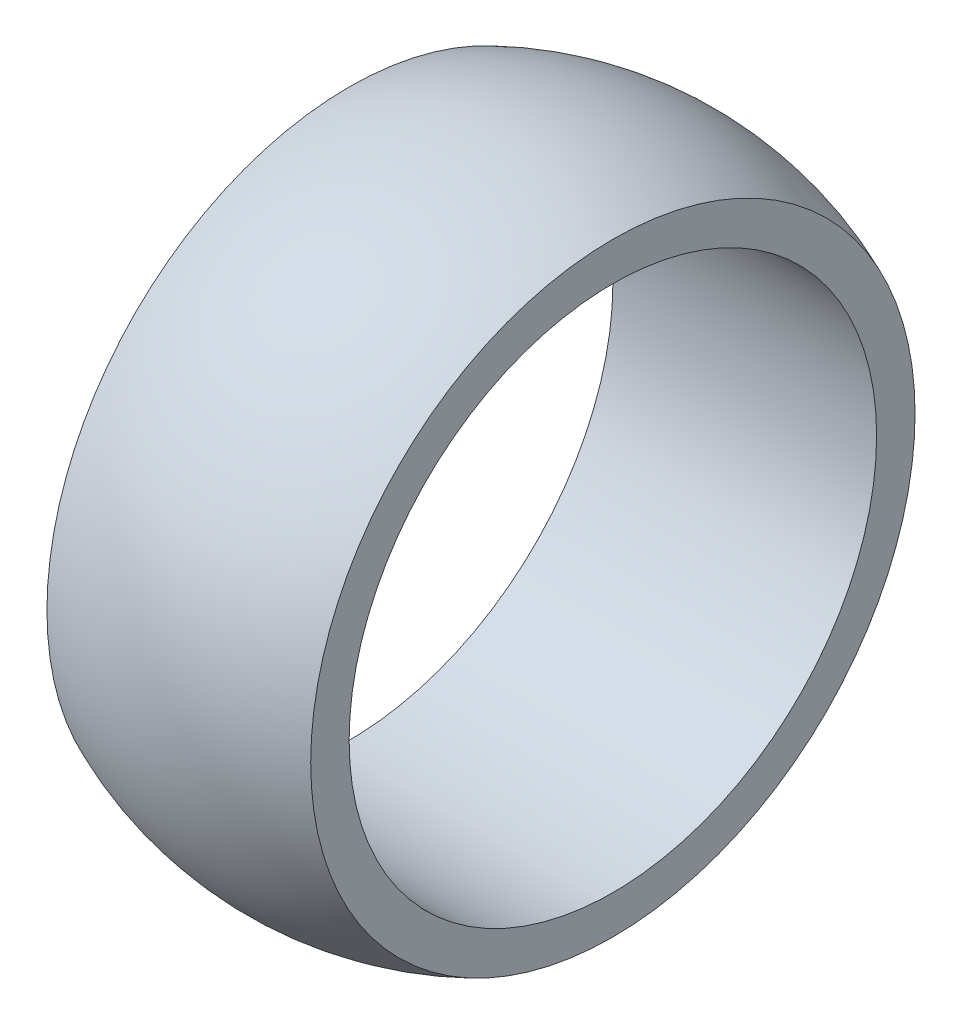
SolidWorks part; units mm, degrees
ref_plane "Front Plane" through (0, 0, 0) normal (0, 0, 1) x (1, 0, 0)
ref_plane "Top Plane" through (0, 0, 0) normal (0, 1, 0) x (1, 0, 0)
ref_plane "Right Plane" through (0, 0, 0) normal (1, 0, 0) x (0, 0, -1)
sketch "Sketch1" plane through (0, 0, 0) normal (0, 1, 0) x (1, 0, 0)
  line L0 (0, 3.175) -> (0, -3.175) construction
  line L1 (0, 3.175) -> (0, -3.175)
  arc A0 (0, 3.175) -> (0, -3.175) centre (0, 0) ccw
  dimension "D1" = 6.35
revolve "Revolve1" add sketch "Sketch1" angle 360 about L0
ref_plane "Plane1" through (4.445, 0, 0) normal (1, 0, 0) x (0, 0, -1)
sketch "Sketch2" plane through (4.445, 0, 0) normal (1, 0, 0) x (0, 0, -1)
  circle A0 centre (0, 0) radius 2.54
  circle A1 centre (0, 0) radius 3.175 construction
  dimension "D1" = 5.08
extrude "Cut-Extrude1" cut sketch "Sketch2" against normal through all both and the other way through all
ref_plane "Plane2" through (6.35, 0, 0) normal (1, 0, 0) x (0, 0, -1)
sketch "Sketch3" plane through (6.35, 0, 0) normal (1, 0, 0) x (0, 0, -1)
  circle A0 centre (0, 0) radius 3.175
  circle A2 centre (0, 0) radius 3.175 construction
extrude "Cut-Extrude2" cut sketch "Sketch3" against normal blind 5.08
mirror "Mirror1" about plane through (0, 0, 0) normal (1, 0, 0) of "Cut-Extrude2"
